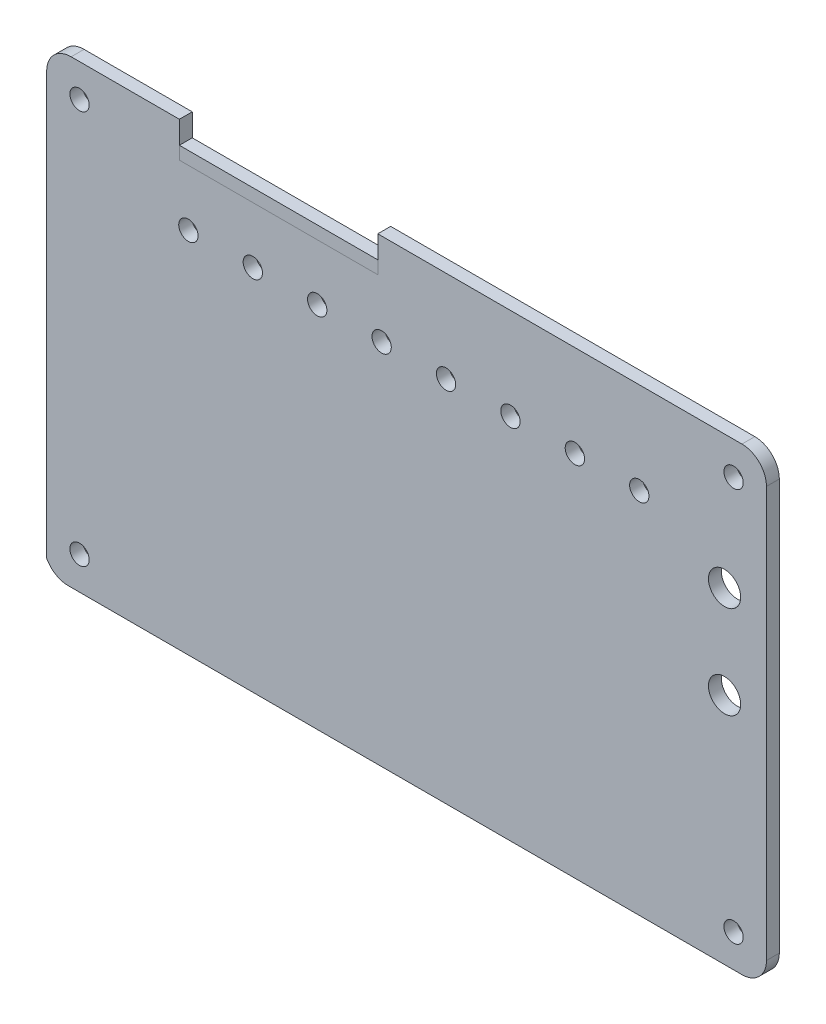
SolidWorks part; units mm, degrees
ref_plane "Спереди" through (0, 0, 0) normal (0, 0, 1) x (1, 0, 0)
ref_plane "Сверху" through (0, 0, 0) normal (0, 1, 0) x (1, 0, 0)
ref_plane "Справа" through (0, 0, 0) normal (1, 0, 0) x (0, 0, -1)
sketch "Skizze1" plane through (0, 0, 0) normal (0, 0, 1) x (1, 0, 0)
  line L5 (-55.3661, -34.0496) -> (-55.3661, 31.4904)
  line L6 (56.3739, 31.4904) -> (56.3739, -32.2496)
  line L7 (-33.3661, 29.7904) -> (-5.3661, 29.7904)
  line L8 (-5.3661, 35.2904) -> (52.5739, 35.2904)
  line L9 (-51.5661, 35.2904) -> (-33.3661, 35.2904)
  line L11 (48.5239, -36.0496) -> (-48.0195, -36.0496)
  line L12 (-33.3661, 35.2904) -> (-33.3661, 29.7904)
  line L13 (-5.3661, 29.7904) -> (-5.3661, 35.2904)
  line L14 (48.5239, -36.0496) -> (52.5739, -36.0496)
  line L15 (-52.0195, -36.0496) -> (-48.0195, -36.0496)
  arc A5 (-51.5661, 35.2904) -> (-55.3661, 31.4904) centre (-51.5661, 31.4904) ccw
  circle A6 centre (-50.2661, 30.1904) radius 1.05
  arc A7 (50.2239, 30.2) -> (52.0132, 29.4449) centre (51.2739, 30.1904) ccw
  arc A8 (52.0132, 29.4449) -> (50.2239, 30.2) centre (51.2739, 30.1904) ccw
  arc A9 (56.3739, 31.4904) -> (52.5739, 35.2904) centre (52.5739, 31.4904) ccw
  arc A14 (-55.3661, -34.0496) -> (-52.0195, -36.0496) centre (-52.0195, -32.2496) ccw
  circle A15 centre (-50.2661, -30.9496) radius 1.05
  circle A16 centre (51.2739, -30.9496) radius 1.05
  arc A17 (52.5739, -36.0496) -> (56.3739, -32.2496) centre (52.5739, -32.2496) ccw
extrude "Aufsatz-Linear austragen1" add sketch "Skizze1" along normal blind 2
sketch "Skizze2" plane through (0, 0, 2) normal (0, 0, 1) x (1, 0, 0)
  line L0 (-55.3661, 31.4904) -> (-55.3661, -34.0496) construction
  circle A0 centre (-33.3661, 21.062) radius 1.5
  circle A1 centre (-23.3661, 21.062) radius 1.5
  circle A2 centre (-13.3661, 21.062) radius 1.5
  circle A3 centre (-3.3661, 21.062) radius 1.5
  circle A4 centre (6.6339, 21.062) radius 1.5
  circle A5 centre (16.6339, 21.062) radius 1.5
  circle A6 centre (26.6339, 21.062) radius 1.5
  circle A7 centre (36.6339, 21.062) radius 1.5
  circle A8 centre (-50.2661, 30.1904) radius 1.5
  circle A9 centre (51.2739, 30.1904) radius 1.5
  circle A10 centre (51.2739, -30.9496) radius 1.5
  circle A11 centre (-50.2661, -30.9496) radius 1.5
  dimension "D1" = 3
  dimension "D2" = 8
  dimension "D3" = 22
extrude "Schnitt-Linear austragen1" cut sketch "Skizze2" against normal blind 2
sketch "Skizze3" plane through (0, 0, 2) normal (0, 0, 1) x (1, 0, 0)
  line L0 (-5.3661, 29.7904) -> (-33.3661, 29.7904) construction
  line L1 (-5.3661, 35.2904) -> (-3.9661, 35.2904)
  line L2 (-5.3661, 35.2904) -> (-5.3661, 29.7904)
  line L3 (-5.3661, 29.7904) -> (-3.9661, 29.7904)
  line L4 (-3.9661, 35.2904) -> (-3.9661, 29.7904)
  line L5 (-33.3661, 35.2904) -> (-34.7661, 35.2904)
  line L6 (-33.3661, 35.2904) -> (-33.3661, 29.7904)
  line L7 (-33.3661, 29.7904) -> (-34.7661, 29.7904)
  line L8 (-34.7661, 35.2904) -> (-34.7661, 29.7904)
  dimension "D1" = 1.4
  dimension "D2" = 1.4
extrude "Schnitt-Linear austragen2" cut sketch "Skizze3" against normal blind 2
sketch "Skizze4" plane through (0, 0, 2) normal (0, 0, 1) x (1, 0, 0)
  line L0 (-34.7661, 35.2904) -> (-34.7661, 29.7904) construction
  line L1 (-3.9661, 29.7904) -> (-34.7661, 29.7904)
  line L2 (-3.9661, 29.7904) -> (-3.9661, 31.7904)
  line L3 (-3.9661, 31.7904) -> (-34.7661, 31.7904)
  line L4 (-34.7661, 29.7904) -> (-34.7661, 31.7904)
  dimension "D1" = 2
extrude "Aufsatz-Linear austragen2" add sketch "Skizze4" against normal blind 2 separate body
sketch "Skizze5" plane through (0, 0, 0) normal (0, 0, 1) x (1, 0, 0)
  line L2 (56.3739, 31.4904) -> (56.3739, -32.2496)
  line L3 (-5.3661, 35.2904) -> (52.5739, 35.2904)
  circle A2 centre (50.409, 0.2414) radius 2
  circle A3 centre (50.427, 14.6328) radius 2
sketch "Skizze6" plane through (0, 0, 2) normal (0, 0, 1) x (1, 0, 0)
  line L0 (-5.3661, 35.2904) -> (52.5739, 35.2904) construction
  line L1 (56.3739, 31.4904) -> (56.3739, -32.2496) construction
  circle A0 centre (49.8739, 14.5904) radius 2.5
  circle A1 centre (49.8739, 0.1816) radius 2.5
  dimension "D1" = 5
  dimension "D2" = 5
  dimension "D3" = 14.4089
  dimension "D4" = 20.7
  dimension "D5" = 6.5
extrude "Schnitt-Linear austragen4" cut sketch "Skizze6" against normal blind 10
